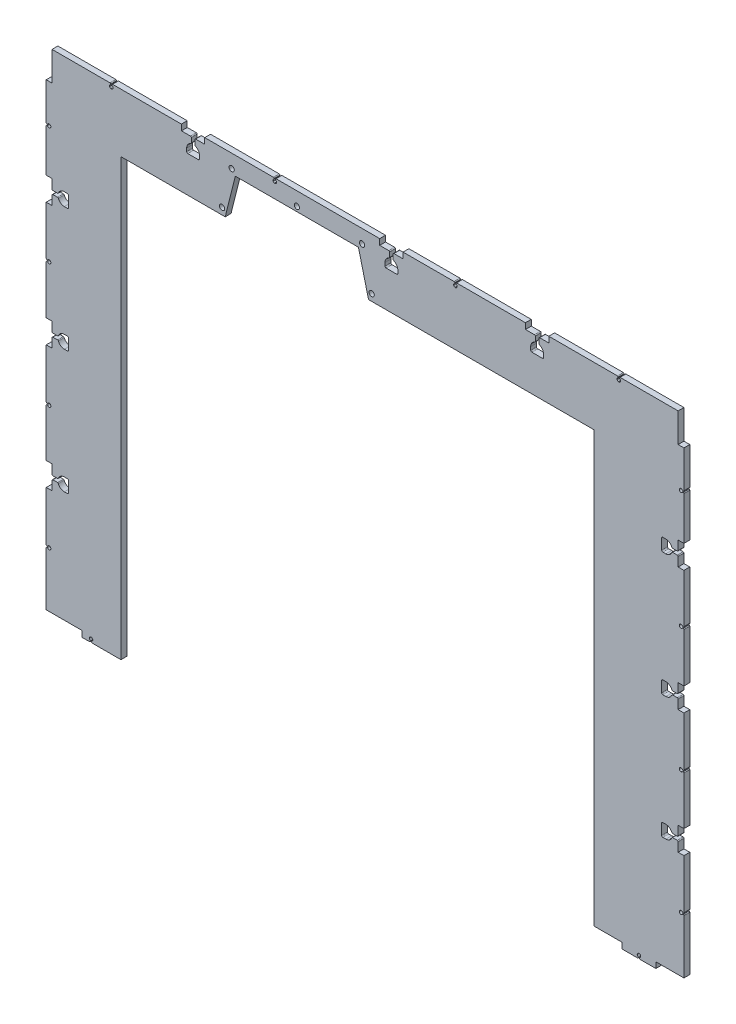
SolidWorks part; units mm, degrees
material "Beech"
ref_plane "Front Plane" through (0, 0, 0) normal (0, 0, 1) x (1, 0, 0)
ref_plane "Top Plane" through (0, 0, 0) normal (0, 1, 0) x (1, 0, 0)
ref_plane "Right Plane" through (0, 0, 0) normal (1, 0, 0) x (0, 0, -1)
sketch "Model" plane through (0, 0, 0) normal (0, 0, 1) x (1, 0, 0)
  line L0 (291.7946, -103.9403) -> (300.4189, -138.4406)
  line L1 (565.4673, -88.4403) -> (515.8475, -88.4403)
  line L2 (570.4673, -145.078) -> (570.4673, -113.3885)
  line L3 (493.4673, -138.4405) -> (300.4189, -138.4406)
  line L4 (569.806, -145.7227) -> (569.7703, -145.7218)
  line L5 (569.7816, -146.711) -> (569.8233, -146.7111)
  line L6 (570.4673, -147.356) -> (570.4673, -184.1903)
  line L7 (570.4673, -184.1903) -> (565.4673, -184.1903)
  line L8 (565.4673, -184.1903) -> (565.4673, -191.9403)
  line L9 (564.7173, -192.6903) -> (560.7929, -192.6901)
  line L10 (554.967, -188.6903) -> (552.3674, -188.6903)
  line L11 (551.3674, -189.6903) -> (551.3674, -198.6903)
  line L12 (552.3674, -199.6903) -> (554.967, -199.6903)
  line L13 (560.7924, -195.6914) -> (564.7171, -195.6905)
  line L14 (565.4673, -196.4405) -> (565.4673, -204.1903)
  line L15 (565.4673, -204.1903) -> (570.4673, -204.1903)
  line L16 (570.4673, -204.1903) -> (570.4673, -245.828)
  line L17 (569.806, -246.4727) -> (569.7703, -246.4718)
  line L18 (569.7816, -247.461) -> (569.8233, -247.4611)
  line L19 (570.4673, -248.106) -> (570.4673, -289.9403)
  line L20 (570.4673, -289.9403) -> (565.4673, -289.9403)
  line L21 (565.4673, -289.9403) -> (565.4673, -297.6903)
  line L22 (564.7173, -298.4403) -> (560.7929, -298.4401)
  line L23 (554.967, -294.4403) -> (552.3674, -294.4403)
  line L24 (551.3674, -295.4403) -> (551.3674, -304.4403)
  line L25 (552.3674, -305.4403) -> (554.967, -305.4403)
  line L26 (560.7924, -301.4414) -> (564.7171, -301.4405)
  line L27 (565.4673, -302.1905) -> (565.4673, -309.9403)
  line L28 (565.4673, -309.9403) -> (570.4673, -309.9403)
  line L29 (570.4673, -309.9403) -> (570.4673, -352.203)
  line L30 (569.806, -352.8477) -> (569.7703, -352.8468)
  line L31 (569.7816, -353.836) -> (569.8233, -353.8361)
  line L32 (570.4673, -354.481) -> (570.4673, -395.6903)
  line L33 (570.4673, -395.6903) -> (565.4673, -395.6903)
  line L34 (565.4673, -395.6903) -> (565.4673, -403.4403)
  line L35 (564.7173, -404.1903) -> (560.7929, -404.1901)
  line L36 (554.967, -400.1903) -> (552.3674, -400.1903)
  line L37 (551.3674, -401.1903) -> (551.3674, -410.1903)
  line L38 (552.3674, -411.1903) -> (554.967, -411.1903)
  line L39 (560.7924, -407.1914) -> (564.7171, -407.1905)
  line L40 (565.4673, -407.9405) -> (565.4673, -415.6903)
  line L41 (565.4673, -415.6903) -> (570.4673, -415.6903)
  line L42 (570.4673, -415.6903) -> (570.4673, -457.953)
  line L43 (569.806, -458.5977) -> (569.7703, -458.5968)
  line L44 (569.7816, -459.586) -> (569.8233, -459.5861)
  line L45 (570.4673, -460.231) -> (570.4673, -506.4403)
  line L46 (570.4673, -506.4403) -> (546.441, -506.4403)
  line L47 (546.441, -506.4403) -> (546.441, -511.4403)
  line L48 (546.441, -511.4403) -> (533.1151, -511.4403)
  line L49 (532.4704, -510.779) -> (532.4713, -510.7432)
  line L50 (531.4821, -510.7545) -> (531.482, -510.7963)
  line L51 (530.8371, -511.4403) -> (517.4936, -511.4403)
  line L52 (517.4936, -511.4403) -> (517.4936, -506.4403)
  line L53 (517.4936, -506.4403) -> (493.4673, -506.4403)
  line L54 (570.4673, -113.3885) -> (565.4673, -113.3885)
  line L55 (565.4673, -113.3885) -> (565.4673, -88.3885)
  line L56 (515.2026, -89.0843) -> (515.2026, -89.1261)
  line L57 (514.2133, -89.1373) -> (514.2142, -89.1016)
  line L58 (513.5696, -88.4403) -> (454.7409, -88.4403)
  line L59 (454.7409, -88.4403) -> (454.7409, -93.4403)
  line L60 (454.7409, -93.4403) -> (446.9911, -93.4403)
  line L61 (446.2411, -94.1905) -> (446.242, -98.1152)
  line L62 (450.2409, -103.9406) -> (450.2409, -106.5403)
  line L63 (449.2409, -107.5403) -> (440.2409, -107.5403)
  line L64 (439.2409, -106.5403) -> (439.2409, -103.9406)
  line L65 (443.2407, -98.1147) -> (443.2409, -94.1903)
  line L66 (442.4909, -93.4403) -> (434.7409, -93.4403)
  line L67 (434.7409, -93.4403) -> (434.7409, -88.4403)
  line L68 (434.7409, -88.4403) -> (375.8947, -88.3885)
  line L69 (375.2498, -89.0325) -> (375.2498, -89.0743)
  line L70 (374.2605, -89.0856) -> (374.2614, -89.0498)
  line L71 (373.6168, -88.3885) -> (329.968, -88.4403)
  line L72 (329.968, -88.4403) -> (329.968, -93.4403)
  line L73 (329.968, -93.4403) -> (322.2182, -93.4403)
  line L74 (321.4682, -94.1905) -> (321.4691, -98.1152)
  line L75 (325.468, -103.9406) -> (325.468, -106.5403)
  line L76 (324.468, -107.5403) -> (315.468, -107.5403)
  line L77 (314.468, -106.5403) -> (314.468, -103.9406)
  line L78 (318.4678, -98.1147) -> (318.468, -94.1903)
  line L79 (317.718, -93.4403) -> (309.968, -93.4403)
  line L80 (309.968, -93.4403) -> (309.968, -88.4403)
  line L81 (309.968, -88.4403) -> (259.896, -88.4403)
  line L83 (261.3074, -103.9403) -> (291.7946, -103.9403)
  line L84 (186.3561, -103.9403) -> (261.3074, -103.9403)
  line L86 (259.896, -88.4403) -> (221.3003, -88.4403)
  line L87 (220.6554, -89.0843) -> (220.6554, -89.1261)
  line L88 (219.6661, -89.1373) -> (219.667, -89.1016)
  line L89 (219.0224, -88.4403) -> (160.1937, -88.4403)
  line L90 (160.1937, -88.4403) -> (160.1937, -93.4403)
  line L91 (160.1937, -93.4403) -> (152.4439, -93.4403)
  line L92 (151.6939, -94.1905) -> (151.6948, -98.1152)
  line L93 (155.6937, -103.9406) -> (155.6937, -106.5403)
  line L94 (154.6937, -107.5403) -> (145.6937, -107.5403)
  line L95 (144.6937, -106.5403) -> (144.6937, -103.9406)
  line L96 (148.6935, -98.1147) -> (148.6937, -94.1903)
  line L97 (147.9437, -93.4403) -> (140.1937, -93.4403)
  line L98 (140.1937, -93.4403) -> (140.1937, -88.4403)
  line L99 (140.1937, -88.4403) -> (81.3475, -88.3885)
  line L100 (80.7026, -89.0325) -> (80.7026, -89.0743)
  line L101 (79.7133, -89.0856) -> (79.7142, -89.0498)
  line L102 (79.0696, -88.3885) -> (29.4673, -88.3885)
  line L103 (177.7313, -138.4404) -> (186.3561, -103.9403)
  line L104 (177.7313, -138.4404) -> (88.4673, -138.4404)
  line L105 (88.4673, -138.4404) -> (88.4673, -189.051)
  line L106 (88.4673, -189.051) -> (88.4673, -506.3791)
  line L107 (88.4673, -506.3791) -> (88.4673, -511.4403)
  line L108 (88.4673, -511.4403) -> (63.9826, -511.4403)
  line L109 (63.3379, -510.779) -> (63.3388, -510.7432)
  line L110 (62.3496, -510.7545) -> (62.3495, -510.7963)
  line L111 (61.7046, -511.4403) -> (54.9676, -511.5889)
  line L112 (54.9676, -511.5889) -> (54.9676, -506.4403)
  line L113 (54.9676, -506.4403) -> (24.4673, -506.4403)
  line L114 (24.4673, -506.4403) -> (24.4673, -460.338)
  line L115 (25.1286, -459.6934) -> (25.1644, -459.6943)
  line L116 (25.1531, -458.705) -> (25.1113, -458.705)
  line L117 (24.4673, -458.0601) -> (24.4673, -415.6903)
  line L118 (24.4673, -415.6903) -> (29.4673, -415.6903)
  line L119 (29.4673, -415.6903) -> (29.4673, -407.9403)
  line L120 (30.2174, -407.1903) -> (34.1417, -407.1905)
  line L121 (39.9676, -411.1903) -> (42.5673, -411.1903)
  line L122 (43.5673, -410.1903) -> (43.5673, -401.1903)
  line L123 (42.5673, -400.1903) -> (39.9676, -400.1903)
  line L124 (34.1422, -404.1892) -> (30.2175, -404.1901)
  line L125 (29.4673, -403.4401) -> (29.4673, -395.6903)
  line L126 (29.4673, -395.6903) -> (24.4673, -395.6903)
  line L127 (24.4673, -395.6903) -> (24.4673, -354.588)
  line L128 (25.1286, -353.9434) -> (25.1644, -353.9443)
  line L129 (25.1531, -352.955) -> (25.1113, -352.955)
  line L130 (24.4673, -352.3101) -> (24.4673, -309.9403)
  line L131 (24.4673, -309.9403) -> (29.4673, -309.9403)
  line L132 (29.4673, -309.9403) -> (29.4673, -302.1903)
  line L133 (30.2173, -301.4403) -> (34.1417, -301.4405)
  line L134 (39.9676, -305.4403) -> (42.5673, -305.4403)
  line L135 (43.5673, -304.4403) -> (43.5673, -295.4403)
  line L136 (42.5673, -294.4403) -> (39.9676, -294.4403)
  line L137 (34.1422, -298.4392) -> (30.2175, -298.4401)
  line L138 (29.4673, -297.6901) -> (29.4673, -289.9403)
  line L139 (29.4673, -289.9403) -> (24.4673, -289.9403)
  line L140 (24.4673, -289.9403) -> (24.4673, -248.213)
  line L141 (25.1286, -247.5684) -> (25.1644, -247.5693)
  line L142 (25.1531, -246.58) -> (25.1113, -246.58)
  line L143 (24.4673, -245.9351) -> (24.4673, -204.1903)
  line L144 (24.4673, -204.1903) -> (29.4673, -204.1903)
  line L145 (29.4673, -204.1903) -> (29.4673, -196.4403)
  line L146 (30.2173, -195.6903) -> (34.1417, -195.6905)
  line L147 (39.9676, -199.6903) -> (42.5673, -199.6903)
  line L148 (43.5673, -198.6903) -> (43.5673, -189.6903)
  line L149 (42.5673, -188.6903) -> (39.9676, -188.6903)
  line L150 (34.1422, -192.6892) -> (30.2175, -192.6901)
  line L151 (29.4673, -191.9401) -> (29.4673, -184.1903)
  line L152 (29.4673, -184.1903) -> (24.4673, -184.1903)
  line L153 (24.4673, -184.1903) -> (24.4673, -147.463)
  line L154 (25.1286, -146.8184) -> (25.1644, -146.8193)
  line L155 (25.1531, -145.83) -> (25.1113, -145.83)
  line L156 (24.4673, -145.1851) -> (24.4673, -113.3885)
  line L157 (29.4673, -88.3885) -> (29.4673, -113.3885)
  line L158 (29.4673, -113.3885) -> (24.4673, -113.3885)
  circle A0 centre (183.233, -99.9404) radius 2.25
  circle A1 centre (175.04, -132.7133) radius 2.25
  circle A2 centre (239.0754, -99.9404) radius 2.25
  circle A3 centre (294.9175, -99.9404) radius 2.25
  circle A4 centre (303.1103, -132.7124) radius 2.25
  spline S0 degree 2 poles (493.4673, -506.4403) (493.4673, -138.4408) (493.4673, -138.4405) knots 0 0 0 1 1 1
  spline S1 degree 3 poles (570.4673, -145.078) (570.4673, -145.4406) (570.1685, -145.732) (569.806, -145.7227) knots 0 0 0 0 1 1 1 1
  spline S2 degree 3 poles (569.7703, -145.7218) (569.5444, -145.7161) (569.3493, -145.5856) (569.2262, -145.3961) knots 2 2 2 2 3 3 3 3
  spline S3 degree 3 poles (569.2262, -145.3961) (568.8939, -144.8844) (568.2582, -144.5881) (567.574, -144.762) knots 3 3 3 3 4 4 4 4
  spline S4 degree 3 poles (567.574, -144.762) (567.0518, -144.8948) (566.6334, -145.3237) (566.5101, -145.8482) knots 4 4 4 4 5 5 5 5
  spline S5 degree 3 poles (566.5101, -145.8482) (566.2783, -146.8344) (567.0203, -147.712) (567.9673, -147.712) knots 5 5 5 5 6 6 6 6
  spline S6 degree 3 poles (567.9673, -147.712) (568.4924, -147.712) (568.9544, -147.4422) (569.2224, -147.0337) knots 6 6 6 6 7 7 7 7
  spline S7 degree 3 poles (569.2224, -147.0337) (569.349, -146.8408) (569.5508, -146.7107) (569.7816, -146.711) knots 7 7 7 7 8 8 8 8
  spline S8 degree 3 poles (569.8233, -146.7111) (570.1791, -146.7116) (570.4673, -147.0002) (570.4673, -147.356) knots 9 9 9 9 10 10 10 10
  spline S9 degree 3 poles (565.4673, -191.9403) (565.4673, -192.3545) (565.1315, -192.6903) (564.7173, -192.6903) knots 13 13 13 13 14 14 14 14
  spline S10 degree 3 poles (560.7929, -192.6901) (560.4851, -192.6896) (560.2096, -192.5006) (560.0987, -192.2135) knots 15 15 15 15 16 16 16 16
  spline S11 degree 3 poles (560.0987, -192.2135) (559.3002, -190.1572) (557.2966, -188.6898) (554.967, -188.6903) knots 16 16 16 16 17 17 17 17
  spline S12 degree 3 poles (552.3674, -188.6903) (551.8151, -188.6903) (551.3674, -189.138) (551.3674, -189.6903) knots 18 18 18 18 19 19 19 19
  spline S13 degree 3 poles (551.3674, -198.6903) (551.3674, -199.2426) (551.8151, -199.6903) (552.3674, -199.6903) knots 20 20 20 20 21 21 21 21
  spline S14 degree 3 poles (554.967, -199.6903) (557.2963, -199.6908) (559.2997, -198.2237) (560.0983, -196.1679) knots 22 22 22 22 23 23 23 23
  spline S15 degree 3 poles (560.0983, -196.1679) (560.2093, -195.8809) (560.4847, -195.6919) (560.7924, -195.6914) knots 23 23 23 23 24 24 24 24
  spline S16 degree 3 poles (564.7171, -195.6905) (565.1314, -195.6904) (565.4673, -196.0262) (565.4673, -196.4405) knots 25 25 25 25 26 26 26 26
  spline S17 degree 3 poles (570.4673, -245.828) (570.4673, -246.1906) (570.1685, -246.482) (569.806, -246.4727) knots 29 29 29 29 30 30 30 30
  spline S18 degree 3 poles (569.7703, -246.4718) (569.5444, -246.4661) (569.3493, -246.3356) (569.2262, -246.1461) knots 31 31 31 31 32 32 32 32
  spline S19 degree 3 poles (569.2262, -246.1461) (568.8939, -245.6344) (568.2582, -245.3381) (567.574, -245.512) knots 32 32 32 32 33 33 33 33
  spline S20 degree 3 poles (567.574, -245.512) (567.0518, -245.6448) (566.6334, -246.0737) (566.5101, -246.5982) knots 33 33 33 33 34 34 34 34
  spline S21 degree 3 poles (566.5101, -246.5982) (566.2783, -247.5844) (567.0203, -248.462) (567.9673, -248.462) knots 34 34 34 34 35 35 35 35
  spline S22 degree 3 poles (567.9673, -248.462) (568.4924, -248.462) (568.9544, -248.1922) (569.2224, -247.7837) knots 35 35 35 35 36 36 36 36
  spline S23 degree 3 poles (569.2224, -247.7837) (569.349, -247.5908) (569.5508, -247.4607) (569.7816, -247.461) knots 36 36 36 36 37 37 37 37
  spline S24 degree 3 poles (569.8233, -247.4611) (570.1791, -247.4616) (570.4673, -247.7502) (570.4673, -248.106) knots 38 38 38 38 39 39 39 39
  spline S25 degree 3 poles (565.4673, -297.6903) (565.4673, -298.1045) (565.1315, -298.4403) (564.7173, -298.4403) knots 42 42 42 42 43 43 43 43
  spline S26 degree 3 poles (560.7929, -298.4401) (560.4851, -298.4396) (560.2096, -298.2506) (560.0987, -297.9635) knots 44 44 44 44 45 45 45 45
  spline S27 degree 3 poles (560.0987, -297.9635) (559.3002, -295.9072) (557.2966, -294.4398) (554.967, -294.4403) knots 45 45 45 45 46 46 46 46
  spline S28 degree 3 poles (552.3674, -294.4403) (551.8151, -294.4403) (551.3674, -294.888) (551.3674, -295.4403) knots 47 47 47 47 48 48 48 48
  spline S29 degree 3 poles (551.3674, -304.4403) (551.3674, -304.9926) (551.8151, -305.4403) (552.3674, -305.4403) knots 49 49 49 49 50 50 50 50
  spline S30 degree 3 poles (554.967, -305.4403) (557.2963, -305.4407) (559.2997, -303.9737) (560.0983, -301.9179) knots 51 51 51 51 52 52 52 52
  spline S31 degree 3 poles (560.0983, -301.9179) (560.2093, -301.6309) (560.4847, -301.4419) (560.7924, -301.4414) knots 52 52 52 52 53 53 53 53
  spline S32 degree 3 poles (564.7171, -301.4405) (565.1314, -301.4404) (565.4673, -301.7762) (565.4673, -302.1905) knots 54 54 54 54 55 55 55 55
  spline S33 degree 3 poles (570.4673, -352.203) (570.4673, -352.5656) (570.1685, -352.857) (569.806, -352.8477) knots 58 58 58 58 59 59 59 59
  spline S34 degree 3 poles (569.7703, -352.8468) (569.5444, -352.8411) (569.3493, -352.7106) (569.2262, -352.5211) knots 60 60 60 60 61 61 61 61
  spline S35 degree 3 poles (569.2262, -352.5211) (568.8939, -352.0094) (568.2582, -351.7131) (567.574, -351.887) knots 61 61 61 61 62 62 62 62
  spline S36 degree 3 poles (567.574, -351.887) (567.0518, -352.0198) (566.6334, -352.4487) (566.5101, -352.9732) knots 62 62 62 62 63 63 63 63
  spline S37 degree 3 poles (566.5101, -352.9732) (566.2783, -353.9595) (567.0203, -354.837) (567.9673, -354.837) knots 63 63 63 63 64 64 64 64
  spline S38 degree 3 poles (567.9673, -354.837) (568.4924, -354.837) (568.9544, -354.5672) (569.2224, -354.1587) knots 64 64 64 64 65 65 65 65
  spline S39 degree 3 poles (569.2224, -354.1587) (569.349, -353.9658) (569.5508, -353.8357) (569.7816, -353.836) knots 65 65 65 65 66 66 66 66
  spline S40 degree 3 poles (569.8233, -353.8361) (570.1791, -353.8366) (570.4673, -354.1252) (570.4673, -354.481) knots 67 67 67 67 68 68 68 68
  spline S41 degree 3 poles (565.4673, -403.4403) (565.4673, -403.8545) (565.1315, -404.1903) (564.7173, -404.1903) knots 71 71 71 71 72 72 72 72
  spline S42 degree 3 poles (560.7929, -404.1901) (560.4851, -404.1896) (560.2096, -404.0006) (560.0987, -403.7135) knots 73 73 73 73 74 74 74 74
  spline S43 degree 3 poles (560.0987, -403.7135) (559.3002, -401.6572) (557.2966, -400.1898) (554.967, -400.1903) knots 74 74 74 74 75 75 75 75
  spline S44 degree 3 poles (552.3674, -400.1903) (551.8151, -400.1903) (551.3674, -400.638) (551.3674, -401.1903) knots 76 76 76 76 77 77 77 77
  spline S45 degree 3 poles (551.3674, -410.1903) (551.3674, -410.7426) (551.8151, -411.1903) (552.3674, -411.1903) knots 78 78 78 78 79 79 79 79
  spline S46 degree 3 poles (554.967, -411.1903) (557.2963, -411.1908) (559.2997, -409.7237) (560.0983, -407.6679) knots 80 80 80 80 81 81 81 81
  spline S47 degree 3 poles (560.0983, -407.6679) (560.2093, -407.3809) (560.4847, -407.1919) (560.7924, -407.1914) knots 81 81 81 81 82 82 82 82
  spline S48 degree 3 poles (564.7171, -407.1905) (565.1314, -407.1904) (565.4673, -407.5262) (565.4673, -407.9405) knots 83 83 83 83 84 84 84 84
  spline S49 degree 3 poles (570.4673, -457.953) (570.4673, -458.3156) (570.1685, -458.607) (569.806, -458.5977) knots 87 87 87 87 88 88 88 88
  spline S50 degree 3 poles (569.7703, -458.5968) (569.5444, -458.5911) (569.3493, -458.4606) (569.2262, -458.2711) knots 89 89 89 89 90 90 90 90
  spline S51 degree 3 poles (569.2262, -458.2711) (568.8939, -457.7594) (568.2582, -457.4631) (567.574, -457.637) knots 90 90 90 90 91 91 91 91
  spline S52 degree 3 poles (567.574, -457.637) (567.0518, -457.7698) (566.6334, -458.1987) (566.5101, -458.7232) knots 91 91 91 91 92 92 92 92
  spline S53 degree 3 poles (566.5101, -458.7232) (566.2783, -459.7094) (567.0203, -460.587) (567.9673, -460.587) knots 92 92 92 92 93 93 93 93
  spline S54 degree 3 poles (567.9673, -460.587) (568.4924, -460.587) (568.9544, -460.3172) (569.2224, -459.9087) knots 93 93 93 93 94 94 94 94
  spline S55 degree 3 poles (569.2224, -459.9087) (569.349, -459.7158) (569.5508, -459.5857) (569.7816, -459.586) knots 94 94 94 94 95 95 95 95
  spline S56 degree 3 poles (569.8233, -459.5861) (570.1791, -459.5866) (570.4673, -459.8752) (570.4673, -460.231) knots 96 96 96 96 97 97 97 97
  spline S57 degree 3 poles (533.1151, -511.4403) (532.7525, -511.4403) (532.4612, -511.1415) (532.4704, -510.779) knots 101 101 101 101 102 102 102 102
  spline S58 degree 3 poles (532.4713, -510.7432) (532.4771, -510.5174) (532.6075, -510.3223) (532.797, -510.1992) knots 103 103 103 103 104 104 104 104
  spline S59 degree 3 poles (532.797, -510.1992) (533.3087, -509.8669) (533.6051, -509.2311) (533.4311, -508.547) knots 104 104 104 104 105 105 105 105
  spline S60 degree 3 poles (533.4311, -508.547) (533.2983, -508.0248) (532.8694, -507.6063) (532.3449, -507.4831) knots 105 105 105 105 106 106 106 106
  spline S61 degree 3 poles (532.3449, -507.4831) (531.3587, -507.2513) (530.4811, -507.9933) (530.4811, -508.9403) knots 106 106 106 106 107 107 107 107
  spline S62 degree 3 poles (530.4811, -508.9403) (530.4811, -509.4654) (530.7509, -509.9274) (531.1594, -510.1954) knots 107 107 107 107 108 108 108 108
  spline S63 degree 3 poles (531.1594, -510.1954) (531.3523, -510.322) (531.4824, -510.5238) (531.4821, -510.7545) knots 108 108 108 108 109 109 109 109
  spline S64 degree 3 poles (531.482, -510.7963) (531.4815, -511.1521) (531.1929, -511.4403) (530.8371, -511.4403) knots 110 110 110 110 111 111 111 111
  spline S65 degree 3 poles (292.6675, -99.9404) (292.6675, -98.6977) (293.6748, -97.6904) (294.9175, -97.6904) (296.1601, -97.6904) (297.1675, -98.6977) (297.1675, -99.9404) knots 2 2 2 2 3 3 3 4 4 4 4 construction
  spline S66 degree 3 poles (297.1675, -99.9404) (297.1675, -101.183) (296.1601, -102.1904) (294.9175, -102.1904) (293.6748, -102.1904) (292.6675, -101.183) (292.6675, -99.9404) knots 0 0 0 0 1 1 1 2 2 2 2 construction
  spline S67 degree 3 poles (300.8603, -132.7124) (300.8603, -131.4698) (301.8677, -130.4624) (303.1103, -130.4624) (304.353, -130.4624) (305.3603, -131.4698) (305.3603, -132.7124) knots 2 2 2 2 3 3 3 4 4 4 4 construction
  spline S68 degree 3 poles (305.3603, -132.7124) (305.3603, -133.9551) (304.353, -134.9624) (303.1103, -134.9624) (301.8677, -134.9624) (300.8603, -133.9551) (300.8603, -132.7124) knots 0 0 0 0 1 1 1 2 2 2 2 construction
  spline S69 degree 3 poles (515.8475, -88.4403) (515.4917, -88.4403) (515.2031, -88.7285) (515.2026, -89.0843) knots 0 0 0 0 1 1 1 1
  spline S70 degree 3 poles (515.2026, -89.1261) (515.2022, -89.3568) (515.3323, -89.5586) (515.5252, -89.6852) knots 2 2 2 2 3 3 3 3
  spline S71 degree 3 poles (515.5252, -89.6852) (515.9337, -89.9532) (516.2035, -90.4152) (516.2035, -90.9403) knots 3 3 3 3 4 4 4 4
  spline S72 degree 3 poles (516.2035, -90.9403) (516.2035, -91.8873) (515.326, -92.6293) (514.3397, -92.3975) knots 4 4 4 4 5 5 5 5
  spline S73 degree 3 poles (514.3397, -92.3975) (513.8152, -92.2742) (513.3863, -91.8558) (513.2535, -91.3336) knots 5 5 5 5 6 6 6 6
  spline S74 degree 3 poles (513.2535, -91.3336) (513.0796, -90.6495) (513.376, -90.0137) (513.8876, -89.6814) knots 6 6 6 6 7 7 7 7
  spline S75 degree 3 poles (513.8876, -89.6814) (514.0771, -89.5583) (514.2076, -89.3632) (514.2133, -89.1373) knots 7 7 7 7 8 8 8 8
  spline S76 degree 3 poles (514.2142, -89.1016) (514.2235, -88.7391) (513.9322, -88.4403) (513.5696, -88.4403) knots 9 9 9 9 10 10 10 10
  spline S77 degree 3 poles (446.9911, -93.4403) (446.5768, -93.4403) (446.241, -93.7762) (446.2411, -94.1905) knots 13 13 13 13 14 14 14 14
  spline S78 degree 3 poles (446.242, -98.1152) (446.2421, -98.4229) (446.4307, -98.6986) (446.7175, -98.81) knots 15 15 15 15 16 16 16 16
  spline S79 degree 3 poles (446.7175, -98.81) (448.7735, -99.6082) (450.2409, -101.6114) (450.2409, -103.9406) knots 16 16 16 16 17 17 17 17
  spline S80 degree 3 poles (450.2409, -106.5403) (450.2409, -107.0925) (449.7932, -107.5403) (449.2409, -107.5403) knots 18 18 18 18 19 19 19 19
  spline S81 degree 3 poles (440.2409, -107.5403) (439.6886, -107.5403) (439.2409, -107.0925) (439.2409, -106.5403) knots 20 20 20 20 21 21 21 21
  spline S82 degree 3 poles (439.2409, -103.9406) (439.2404, -101.6111) (440.7078, -99.6074) (442.7641, -98.8089) knots 22 22 22 22 23 23 23 23
  spline S83 degree 3 poles (442.7641, -98.8089) (443.0512, -98.698) (443.2402, -98.4225) (443.2407, -98.1147) knots 23 23 23 23 24 24 24 24
  spline S84 degree 3 poles (443.2409, -94.1903) (443.2409, -93.7761) (442.9051, -93.4403) (442.4909, -93.4403) knots 25 25 25 25 26 26 26 26
  spline S85 degree 3 poles (375.8947, -88.3885) (375.5389, -88.3885) (375.2503, -88.6767) (375.2498, -89.0325) knots 29 29 29 29 30 30 30 30
  spline S86 degree 3 poles (375.2498, -89.0743) (375.2494, -89.305) (375.3795, -89.5069) (375.5724, -89.6334) knots 31 31 31 31 32 32 32 32
  spline S87 degree 3 poles (375.5724, -89.6334) (375.981, -89.9014) (376.2507, -90.3635) (376.2507, -90.8885) knots 32 32 32 32 33 33 33 33
  spline S88 degree 3 poles (376.2507, -90.8885) (376.2507, -91.8355) (375.3732, -92.5776) (374.3869, -92.3458) knots 33 33 33 33 34 34 34 34
  spline S89 degree 3 poles (374.3869, -92.3458) (373.8624, -92.2225) (373.4335, -91.804) (373.3007, -91.2819) knots 34 34 34 34 35 35 35 35
  spline S90 degree 3 poles (373.3007, -91.2819) (373.1268, -90.5977) (373.4232, -89.9619) (373.9348, -89.6296) knots 35 35 35 35 36 36 36 36
  spline S91 degree 3 poles (373.9348, -89.6296) (374.1243, -89.5066) (374.2548, -89.3115) (374.2605, -89.0856) knots 36 36 36 36 37 37 37 37
  spline S92 degree 3 poles (374.2614, -89.0498) (374.2707, -88.6874) (373.9794, -88.3885) (373.6168, -88.3885) knots 38 38 38 38 39 39 39 39
  spline S93 degree 3 poles (322.2182, -93.4403) (321.8039, -93.4403) (321.4681, -93.7762) (321.4682, -94.1905) knots 42 42 42 42 43 43 43 43
  spline S94 degree 3 poles (321.4691, -98.1152) (321.4692, -98.4229) (321.6577, -98.6986) (321.9446, -98.81) knots 44 44 44 44 45 45 45 45
  spline S95 degree 3 poles (321.9446, -98.81) (324.0006, -99.6082) (325.468, -101.6114) (325.468, -103.9406) knots 45 45 45 45 46 46 46 46
  spline S96 degree 3 poles (325.468, -106.5403) (325.468, -107.0925) (325.0203, -107.5403) (324.468, -107.5403) knots 47 47 47 47 48 48 48 48
  spline S97 degree 3 poles (315.468, -107.5403) (314.9157, -107.5403) (314.468, -107.0925) (314.468, -106.5403) knots 49 49 49 49 50 50 50 50
  spline S98 degree 3 poles (314.468, -103.9406) (314.4675, -101.6111) (315.9349, -99.6074) (317.9912, -98.8089) knots 51 51 51 51 52 52 52 52
  spline S99 degree 3 poles (317.9912, -98.8089) (318.2783, -98.698) (318.4673, -98.4225) (318.4678, -98.1147) knots 52 52 52 52 53 53 53 53
  spline S100 degree 3 poles (318.468, -94.1903) (318.468, -93.7761) (318.1322, -93.4403) (317.718, -93.4403) knots 54 54 54 54 55 55 55 55
  spline S101 degree 3 poles (221.3003, -88.4403) (220.9445, -88.4403) (220.6559, -88.7285) (220.6554, -89.0843) knots 3 3 3 3 4 4 4 4
  spline S102 degree 3 poles (220.6554, -89.1261) (220.655, -89.3568) (220.7851, -89.5586) (220.978, -89.6852) knots 5 5 5 5 6 6 6 6
  spline S103 degree 3 poles (220.978, -89.6852) (221.3865, -89.9532) (221.6563, -90.4152) (221.6563, -90.9403) knots 6 6 6 6 7 7 7 7
  spline S104 degree 3 poles (221.6563, -90.9403) (221.6563, -91.8873) (220.7788, -92.6293) (219.7925, -92.3975) knots 7 7 7 7 8 8 8 8
  spline S105 degree 3 poles (219.7925, -92.3975) (219.268, -92.2742) (218.8391, -91.8558) (218.7063, -91.3336) knots 8 8 8 8 9 9 9 9
  spline S106 degree 3 poles (218.7063, -91.3336) (218.5324, -90.6495) (218.8288, -90.0137) (219.3404, -89.6814) knots 9 9 9 9 10 10 10 10
  spline S107 degree 3 poles (219.3404, -89.6814) (219.5299, -89.5583) (219.6604, -89.3632) (219.6661, -89.1373) knots 10 10 10 10 11 11 11 11
  spline S108 degree 3 poles (219.667, -89.1016) (219.6763, -88.7391) (219.3849, -88.4403) (219.0224, -88.4403) knots 12 12 12 12 13 13 13 13
  spline S109 degree 3 poles (152.4439, -93.4403) (152.0296, -93.4403) (151.6938, -93.7762) (151.6939, -94.1905) knots 16 16 16 16 17 17 17 17
  spline S110 degree 3 poles (151.6948, -98.1152) (151.6949, -98.4229) (151.8834, -98.6986) (152.1703, -98.81) knots 18 18 18 18 19 19 19 19
  spline S111 degree 3 poles (152.1703, -98.81) (154.2263, -99.6082) (155.6937, -101.6114) (155.6937, -103.9406) knots 19 19 19 19 20 20 20 20
  spline S112 degree 3 poles (155.6937, -106.5403) (155.6937, -107.0925) (155.246, -107.5403) (154.6937, -107.5403) knots 21 21 21 21 22 22 22 22
  spline S113 degree 3 poles (145.6937, -107.5403) (145.1414, -107.5403) (144.6937, -107.0925) (144.6937, -106.5403) knots 23 23 23 23 24 24 24 24
  spline S114 degree 3 poles (144.6937, -103.9406) (144.6937, -101.6111) (146.1615, -99.6077) (148.2179, -98.8097) knots 25 25 25 25 26 26 26 26
  spline S115 degree 3 poles (148.2179, -98.8097) (148.5049, -98.6983) (148.6935, -98.4225) (148.6935, -98.1147) knots 26 26 26 26 27 27 27 27
  spline S116 degree 3 poles (148.6937, -94.1903) (148.6937, -93.7761) (148.3579, -93.4403) (147.9437, -93.4403) knots 28 28 28 28 29 29 29 29
  spline S117 degree 3 poles (81.3475, -88.3885) (80.9917, -88.3885) (80.7031, -88.6767) (80.7026, -89.0325) knots 32 32 32 32 33 33 33 33
  spline S118 degree 3 poles (80.7026, -89.0743) (80.7022, -89.305) (80.8323, -89.5069) (81.0252, -89.6334) knots 34 34 34 34 35 35 35 35
  spline S119 degree 3 poles (81.0252, -89.6334) (81.4337, -89.9014) (81.7035, -90.3635) (81.7035, -90.8885) knots 35 35 35 35 36 36 36 36
  spline S120 degree 3 poles (81.7035, -90.8885) (81.7035, -91.8355) (80.826, -92.5776) (79.8397, -92.3458) knots 36 36 36 36 37 37 37 37
  spline S121 degree 3 poles (79.8397, -92.3458) (79.3152, -92.2225) (78.8863, -91.804) (78.7535, -91.2819) knots 37 37 37 37 38 38 38 38
  spline S122 degree 3 poles (78.7535, -91.2819) (78.5796, -90.5977) (78.876, -89.9619) (79.3876, -89.6296) knots 38 38 38 38 39 39 39 39
  spline S123 degree 3 poles (79.3876, -89.6296) (79.5771, -89.5066) (79.7076, -89.3115) (79.7133, -89.0856) knots 39 39 39 39 40 40 40 40
  spline S124 degree 3 poles (79.7142, -89.0498) (79.7235, -88.6874) (79.4322, -88.3885) (79.0696, -88.3885) knots 41 41 41 41 42 42 42 42
  spline S125 degree 3 poles (63.9826, -511.4403) (63.62, -511.4403) (63.3287, -511.1415) (63.3379, -510.779) knots 5 5 5 5 6 6 6 6
  spline S126 degree 3 poles (63.3388, -510.7432) (63.3446, -510.5174) (63.475, -510.3223) (63.6645, -510.1992) knots 7 7 7 7 8 8 8 8
  spline S127 degree 3 poles (63.6645, -510.1992) (64.1762, -509.8669) (64.4725, -509.2311) (64.2986, -508.547) knots 8 8 8 8 9 9 9 9
  spline S128 degree 3 poles (64.2986, -508.547) (64.1658, -508.0248) (63.7369, -507.6063) (63.2124, -507.4831) knots 9 9 9 9 10 10 10 10
  spline S129 degree 3 poles (63.2124, -507.4831) (62.2262, -507.2513) (61.3486, -507.9933) (61.3486, -508.9403) knots 10 10 10 10 11 11 11 11
  spline S130 degree 3 poles (61.3486, -508.9403) (61.3486, -509.4654) (61.6184, -509.9274) (62.0269, -510.1954) knots 11 11 11 11 12 12 12 12
  spline S131 degree 3 poles (62.0269, -510.1954) (62.2198, -510.322) (62.3499, -510.5238) (62.3496, -510.7545) knots 12 12 12 12 13 13 13 13
  spline S132 degree 3 poles (62.3495, -510.7963) (62.349, -511.1521) (62.0604, -511.4403) (61.7046, -511.4403) knots 14 14 14 14 15 15 15 15
  spline S133 degree 3 poles (24.4673, -460.338) (24.4673, -459.9754) (24.7662, -459.6841) (25.1286, -459.6934) knots 19 19 19 19 20 20 20 20
  spline S134 degree 3 poles (25.1644, -459.6943) (25.3903, -459.7) (25.5853, -459.8305) (25.7084, -460.02) knots 21 21 21 21 22 22 22 22
  spline S135 degree 3 poles (25.7084, -460.02) (26.0407, -460.5316) (26.6765, -460.828) (27.3607, -460.6541) knots 22 22 22 22 23 23 23 23
  spline S136 degree 3 poles (27.3607, -460.6541) (27.8828, -460.5213) (28.3013, -460.0924) (28.4245, -459.5679) knots 23 23 23 23 24 24 24 24
  spline S137 degree 3 poles (28.4245, -459.5679) (28.6563, -458.5816) (27.9143, -457.7041) (26.9673, -457.7041) knots 24 24 24 24 25 25 25 25
  spline S138 degree 3 poles (26.9673, -457.7041) (26.4422, -457.7041) (25.9802, -457.9739) (25.7122, -458.3824) knots 25 25 25 25 26 26 26 26
  spline S139 degree 3 poles (25.7122, -458.3824) (25.5856, -458.5753) (25.3838, -458.7054) (25.1531, -458.705) knots 26 26 26 26 27 27 27 27
  spline S140 degree 3 poles (25.1113, -458.705) (24.7555, -458.7045) (24.4673, -458.4159) (24.4673, -458.0601) knots 28 28 28 28 29 29 29 29
  spline S141 degree 3 poles (29.4673, -407.9403) (29.4673, -407.5261) (29.8031, -407.1903) (30.2174, -407.1903) knots 32 32 32 32 33 33 33 33
  spline S142 degree 3 poles (34.1417, -407.1905) (34.4495, -407.1905) (34.7253, -407.3791) (34.8367, -407.6661) knots 34 34 34 34 35 35 35 35
  spline S143 degree 3 poles (34.8367, -407.6661) (35.6347, -409.7225) (37.6381, -411.1903) (39.9676, -411.1903) knots 35 35 35 35 36 36 36 36
  spline S144 degree 3 poles (42.5673, -411.1903) (43.1196, -411.1903) (43.5673, -410.7426) (43.5673, -410.1903) knots 37 37 37 37 38 38 38 38
  spline S145 degree 3 poles (43.5673, -401.1903) (43.5673, -400.638) (43.1196, -400.1903) (42.5673, -400.1903) knots 39 39 39 39 40 40 40 40
  spline S146 degree 3 poles (39.9676, -400.1903) (37.6384, -400.1903) (35.6352, -401.6577) (34.837, -403.7137) knots 41 41 41 41 42 42 42 42
  spline S147 degree 3 poles (34.837, -403.7137) (34.7256, -404.0006) (34.4499, -404.1891) (34.1422, -404.1892) knots 42 42 42 42 43 43 43 43
  spline S148 degree 3 poles (30.2175, -404.1901) (29.8032, -404.1902) (29.4673, -403.8544) (29.4673, -403.4401) knots 44 44 44 44 45 45 45 45
  spline S149 degree 3 poles (24.4673, -354.588) (24.4673, -354.2254) (24.7662, -353.9341) (25.1286, -353.9434) knots 48 48 48 48 49 49 49 49
  spline S150 degree 3 poles (25.1644, -353.9443) (25.3903, -353.95) (25.5853, -354.0805) (25.7084, -354.27) knots 50 50 50 50 51 51 51 51
  spline S151 degree 3 poles (25.7084, -354.27) (26.0407, -354.7816) (26.6765, -355.078) (27.3607, -354.9041) knots 51 51 51 51 52 52 52 52
  spline S152 degree 3 poles (27.3607, -354.9041) (27.8828, -354.7713) (28.3013, -354.3424) (28.4245, -353.8179) knots 52 52 52 52 53 53 53 53
  spline S153 degree 3 poles (28.4245, -353.8179) (28.6563, -352.8316) (27.9143, -351.9541) (26.9673, -351.9541) knots 53 53 53 53 54 54 54 54
  spline S154 degree 3 poles (26.9673, -351.9541) (26.4422, -351.9541) (25.9802, -352.2239) (25.7122, -352.6324) knots 54 54 54 54 55 55 55 55
  spline S155 degree 3 poles (25.7122, -352.6324) (25.5856, -352.8253) (25.3838, -352.9554) (25.1531, -352.955) knots 55 55 55 55 56 56 56 56
  spline S156 degree 3 poles (25.1113, -352.955) (24.7555, -352.9545) (24.4673, -352.6659) (24.4673, -352.3101) knots 57 57 57 57 58 58 58 58
  spline S157 degree 3 poles (29.4673, -302.1903) (29.4673, -301.7761) (29.8031, -301.4403) (30.2173, -301.4403) knots 61 61 61 61 62 62 62 62
  spline S158 degree 3 poles (34.1417, -301.4405) (34.4495, -301.4405) (34.7253, -301.6291) (34.8367, -301.9161) knots 63 63 63 63 64 64 64 64
  spline S159 degree 3 poles (34.8367, -301.9161) (35.6347, -303.9725) (37.6381, -305.4403) (39.9676, -305.4403) knots 64 64 64 64 65 65 65 65
  spline S160 degree 3 poles (42.5673, -305.4403) (43.1196, -305.4403) (43.5673, -304.9926) (43.5673, -304.4403) knots 66 66 66 66 67 67 67 67
  spline S161 degree 3 poles (43.5673, -295.4403) (43.5673, -294.888) (43.1196, -294.4403) (42.5673, -294.4403) knots 68 68 68 68 69 69 69 69
  spline S162 degree 3 poles (39.9676, -294.4403) (37.6384, -294.4403) (35.6352, -295.9077) (34.837, -297.9637) knots 70 70 70 70 71 71 71 71
  spline S163 degree 3 poles (34.837, -297.9637) (34.7256, -298.2506) (34.4499, -298.4391) (34.1422, -298.4392) knots 71 71 71 71 72 72 72 72
  spline S164 degree 3 poles (30.2175, -298.4401) (29.8032, -298.4402) (29.4673, -298.1044) (29.4673, -297.6901) knots 73 73 73 73 74 74 74 74
  spline S165 degree 3 poles (24.4673, -248.213) (24.4673, -247.8505) (24.7662, -247.5591) (25.1286, -247.5684) knots 77 77 77 77 78 78 78 78
  spline S166 degree 3 poles (25.1644, -247.5693) (25.3903, -247.575) (25.5853, -247.7055) (25.7084, -247.895) knots 79 79 79 79 80 80 80 80
  spline S167 degree 3 poles (25.7084, -247.895) (26.0407, -248.4066) (26.6765, -248.703) (27.3607, -248.5291) knots 80 80 80 80 81 81 81 81
  spline S168 degree 3 poles (27.3607, -248.5291) (27.8828, -248.3963) (28.3013, -247.9674) (28.4245, -247.4429) knots 81 81 81 81 82 82 82 82
  spline S169 degree 3 poles (28.4245, -247.4429) (28.6563, -246.4566) (27.9143, -245.5791) (26.9673, -245.5791) knots 82 82 82 82 83 83 83 83
  spline S170 degree 3 poles (26.9673, -245.5791) (26.4422, -245.5791) (25.9802, -245.8489) (25.7122, -246.2574) knots 83 83 83 83 84 84 84 84
  spline S171 degree 3 poles (25.7122, -246.2574) (25.5856, -246.4503) (25.3838, -246.5804) (25.1531, -246.58) knots 84 84 84 84 85 85 85 85
  spline S172 degree 3 poles (25.1113, -246.58) (24.7555, -246.5795) (24.4673, -246.2909) (24.4673, -245.9351) knots 86 86 86 86 87 87 87 87
  spline S173 degree 3 poles (29.4673, -196.4403) (29.4673, -196.0261) (29.8031, -195.6903) (30.2173, -195.6903) knots 90 90 90 90 91 91 91 91
  spline S174 degree 3 poles (34.1417, -195.6905) (34.4495, -195.6905) (34.7253, -195.8791) (34.8367, -196.1661) knots 92 92 92 92 93 93 93 93
  spline S175 degree 3 poles (34.8367, -196.1661) (35.6347, -198.2225) (37.6381, -199.6903) (39.9676, -199.6903) knots 93 93 93 93 94 94 94 94
  spline S176 degree 3 poles (42.5673, -199.6903) (43.1196, -199.6903) (43.5673, -199.2426) (43.5673, -198.6903) knots 95 95 95 95 96 96 96 96
  spline S177 degree 3 poles (43.5673, -189.6903) (43.5673, -189.138) (43.1196, -188.6903) (42.5673, -188.6903) knots 97 97 97 97 98 98 98 98
  spline S178 degree 3 poles (39.9676, -188.6903) (37.6384, -188.6903) (35.6352, -190.1577) (34.837, -192.2137) knots 99 99 99 99 100 100 100 100
  spline S179 degree 3 poles (34.837, -192.2137) (34.7256, -192.5006) (34.4499, -192.6891) (34.1422, -192.6892) knots 100 100 100 100 101 101 101 101
  spline S180 degree 3 poles (30.2175, -192.6901) (29.8032, -192.6902) (29.4673, -192.3544) (29.4673, -191.9401) knots 102 102 102 102 103 103 103 103
  spline S181 degree 3 poles (24.4673, -147.463) (24.4673, -147.1004) (24.7662, -146.8091) (25.1286, -146.8184) knots 106 106 106 106 107 107 107 107
  spline S182 degree 3 poles (25.1644, -146.8193) (25.3903, -146.825) (25.5853, -146.9555) (25.7084, -147.145) knots 108 108 108 108 109 109 109 109
  spline S183 degree 3 poles (25.7084, -147.145) (26.0407, -147.6566) (26.6765, -147.953) (27.3607, -147.7791) knots 109 109 109 109 110 110 110 110
  spline S184 degree 3 poles (27.3607, -147.7791) (27.8828, -147.6463) (28.3013, -147.2174) (28.4245, -146.6929) knots 110 110 110 110 111 111 111 111
  spline S185 degree 3 poles (28.4245, -146.6929) (28.6563, -145.7066) (27.9143, -144.8291) (26.9673, -144.8291) knots 111 111 111 111 112 112 112 112
  spline S186 degree 3 poles (26.9673, -144.8291) (26.4422, -144.8291) (25.9802, -145.0989) (25.7122, -145.5074) knots 112 112 112 112 113 113 113 113
  spline S187 degree 3 poles (25.7122, -145.5074) (25.5856, -145.7003) (25.3838, -145.8304) (25.1531, -145.83) knots 113 113 113 113 114 114 114 114
  spline S188 degree 3 poles (25.1113, -145.83) (24.7555, -145.8295) (24.4673, -145.5409) (24.4673, -145.1851) knots 115 115 115 115 116 116 116 116
  spline S189 degree 3 poles (180.983, -99.9404) (180.983, -98.6977) (181.9903, -97.6904) (183.233, -97.6904) (184.4756, -97.6904) (185.483, -98.6977) (185.483, -99.9404) knots 2 2 2 2 3 3 3 4 4 4 4 construction
  spline S190 degree 3 poles (185.483, -99.9404) (185.483, -101.183) (184.4756, -102.1904) (183.233, -102.1904) (181.9903, -102.1904) (180.983, -101.183) (180.983, -99.9404) knots 0 0 0 0 1 1 1 2 2 2 2 construction
  spline S191 degree 3 poles (236.8254, -99.9404) (236.8254, -98.6977) (237.8327, -97.6904) (239.0754, -97.6904) (240.318, -97.6904) (241.3254, -98.6977) (241.3254, -99.9404) knots 2 2 2 2 3 3 3 4 4 4 4 construction
  spline S192 degree 3 poles (241.3254, -99.9404) (241.3254, -101.183) (240.318, -102.1904) (239.0754, -102.1904) (237.8327, -102.1904) (236.8254, -101.183) (236.8254, -99.9404) knots 0 0 0 0 1 1 1 2 2 2 2 construction
  spline S193 degree 3 poles (172.79, -132.7133) (172.79, -131.4706) (173.7973, -130.4633) (175.04, -130.4633) (176.2826, -130.4633) (177.29, -131.4706) (177.29, -132.7133) knots 2 2 2 2 3 3 3 4 4 4 4 construction
  spline S194 degree 3 poles (177.29, -132.7133) (177.29, -133.9559) (176.2826, -134.9633) (175.04, -134.9633) (173.7973, -134.9633) (172.79, -133.9559) (172.79, -132.7133) knots 0 0 0 0 1 1 1 2 2 2 2 construction
  dimension "D2" = 423
extrude "Boss-Extrude1" add sketch "Model" along normal blind 5 contours S188 L155 S187 S186 S185 S184 S183 S182 L154 S181 L153 L152 L151 S180 L150 S179 S178 L149 S177 L148 S176 L147 S175 S174 L146 S173 L145 L144 L143 S172 L142 S171 S170 S169 S168 S167 S166 L141 S165 L140 L139 L138 S164 L137 S163 S162 L136 S161 L135 S160 L134
